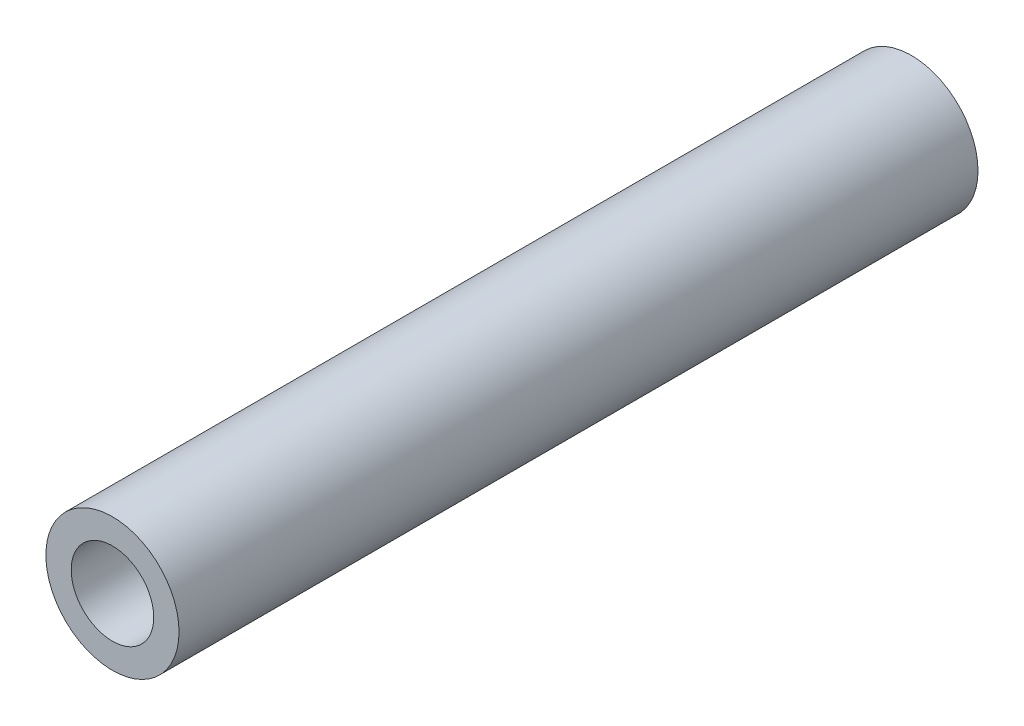
SolidWorks part; units mm, degrees
material "7050-T73510"
ref_plane "前视基准面" through (0, 0, 0) normal (0, 0, 1) x (1, 0, 0)
ref_plane "上视基准面" through (0, 0, 0) normal (0, 1, 0) x (1, 0, 0)
ref_plane "右视基准面" through (0, 0, 0) normal (1, 0, 0) x (0, 0, -1)
sketch "草图1" plane through (0, 0, 0) normal (0, 0, 1) x (1, 0, 0)
  circle A0 centre (0, 0) radius 2.5
  circle A1 centre (0, 0) radius 1.55
  dimension "D1" = 3.1
  dimension "D2" = 5
extrude "凸台-拉伸1" add sketch "草图1" along normal blind 30
